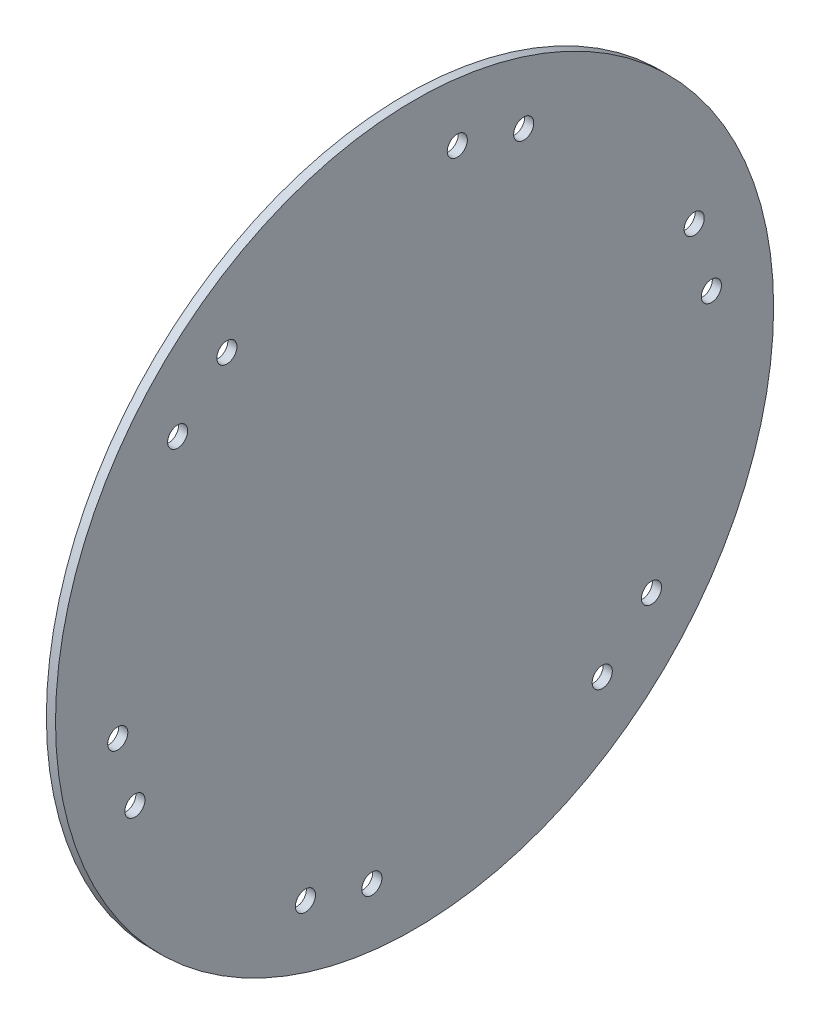
SolidWorks part; units mm, degrees
material "Oak"
ref_plane "Front Plane" through (0, 0, 0) normal (0, 0, 1) x (1, 0, 0)
ref_plane "Top Plane" through (0, 0, 0) normal (0, 1, 0) x (1, 0, 0)
ref_plane "Right Plane" through (0, 0, 0) normal (1, 0, 0) x (0, 0, -1)
sketch "Sketch2" plane through (0, 0, 0) normal (1, 0, 0) x (0, 0, -1)
  circle A0 centre (0, 0) radius 125
  dimension "D1" = 250
extrude "Boss-Extrude1" add sketch "Sketch2" along normal blind 3.18
sketch "Sketch3" plane through (0, 0, 0) normal (-1, 0, 0) x (0, 0, 1)
  circle A5 centre (103.3291, -15.785) radius 3.5
  circle A12 centre (97.3419, -39.0262) radius 3.5
  circle A13 centre (14.8733, -103.8137) radius 3.5
  circle A14 centre (37.9943, -97.3781) radius 3.5
  circle A15 centre (-65.3347, -81.5931) radius 3.5
  circle A16 centre (-82.4687, -64.7875) radius 3.5
  circle A17 centre (-97.3419, 39.0262) radius 3.5
  circle A18 centre (-103.3291, 15.785) radius 3.5
  circle A19 centre (-37.9943, 97.3781) radius 3.5
  circle A20 centre (-14.8733, 103.8137) radius 3.5
  circle A21 centre (65.3347, 81.5931) radius 3.5
  circle A22 centre (82.4687, 64.7875) radius 3.5
  dimension "D1" = 7
extrude "Cut-Extrude1" cut sketch "Sketch3" against normal through all
